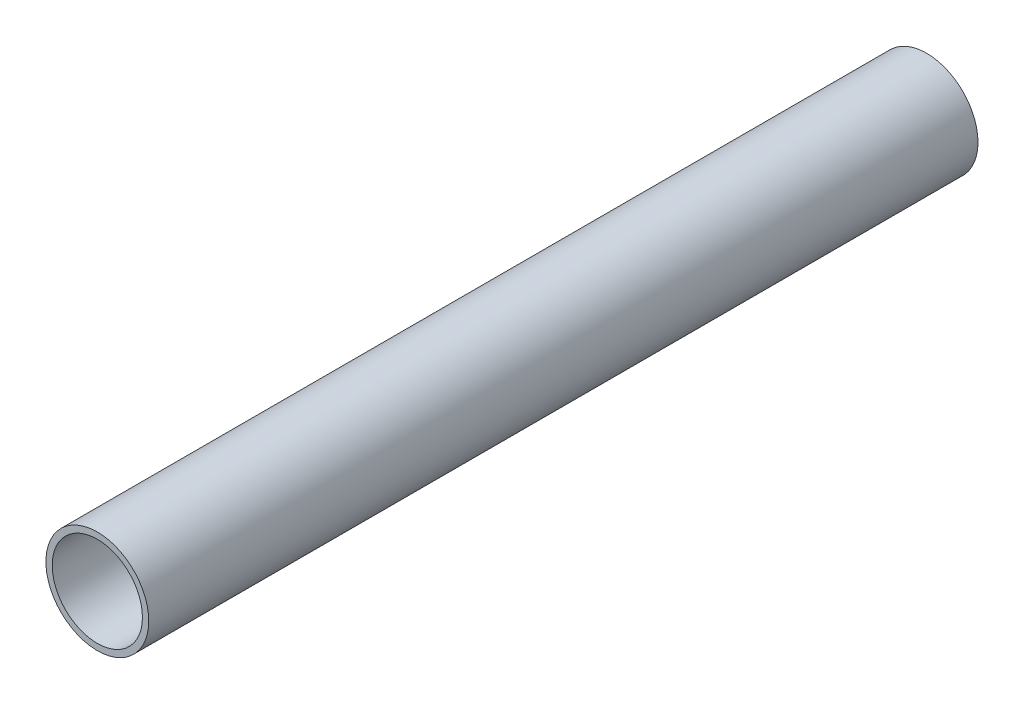
SolidWorks part; units mm, degrees
material "Corrugated Paper"
ref_plane "Front Plane" through (0, 0, 0) normal (0, 0, 1) x (1, 0, 0)
ref_plane "Top Plane" through (0, 0, 0) normal (0, 1, 0) x (1, 0, 0)
ref_plane "Right Plane" through (0, 0, 0) normal (1, 0, 0) x (0, 0, -1)
sketch "Sketch1" plane through (0, 0, 0) normal (0, 0, 1) x (1, 0, 0)
  circle A0 centre (0, 0) radius 2.72
  circle A1 centre (0, 0) radius 3.1
  dimension "D1" = 5.44
  dimension "D2" = 6.2
extrude "Boss-Extrude1" add sketch "Sketch1" along normal mid plane 50
